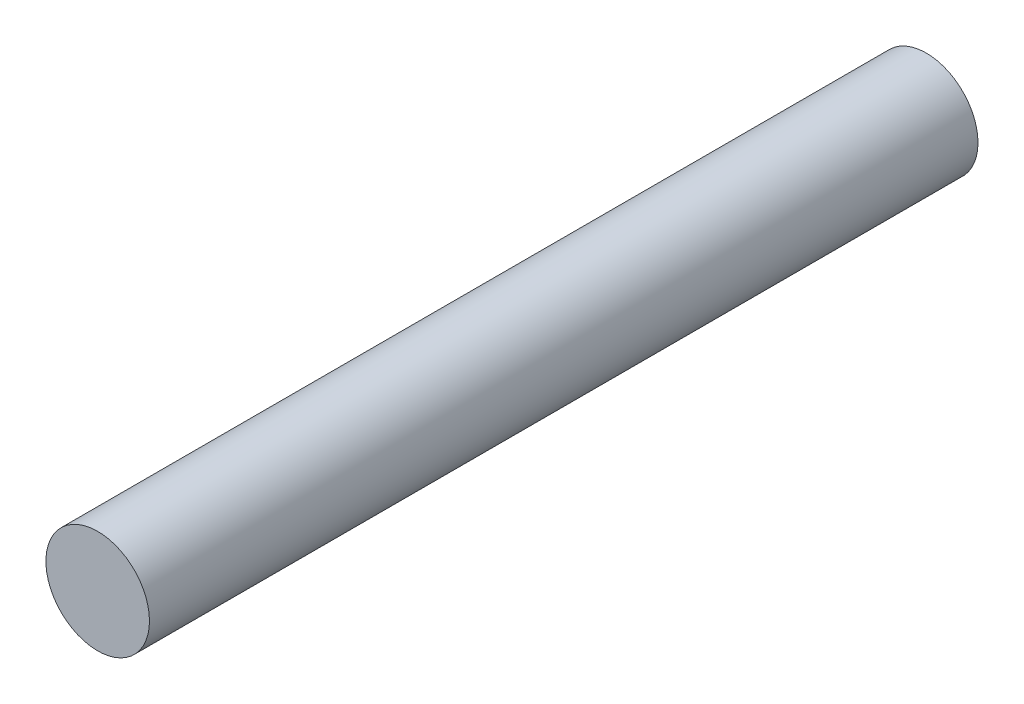
SolidWorks part; units mm, degrees
material "1.4000 (X6Cr13)"
ref_plane "Plan de face" through (0, 0, 0) normal (0, 0, 1) x (1, 0, 0)
ref_plane "Plan de dessus" through (0, 0, 0) normal (0, 1, 0) x (1, 0, 0)
ref_plane "Plan de droite" through (0, 0, 0) normal (1, 0, 0) x (0, 0, -1)
sketch "Esquisse1" plane through (0, 0, 0) normal (0, 0, 1) x (1, 0, 0)
  circle A0 centre (0, 0) radius 2.5
extrude "Boss.-Extru.1" add sketch "Esquisse1" along normal blind 40
